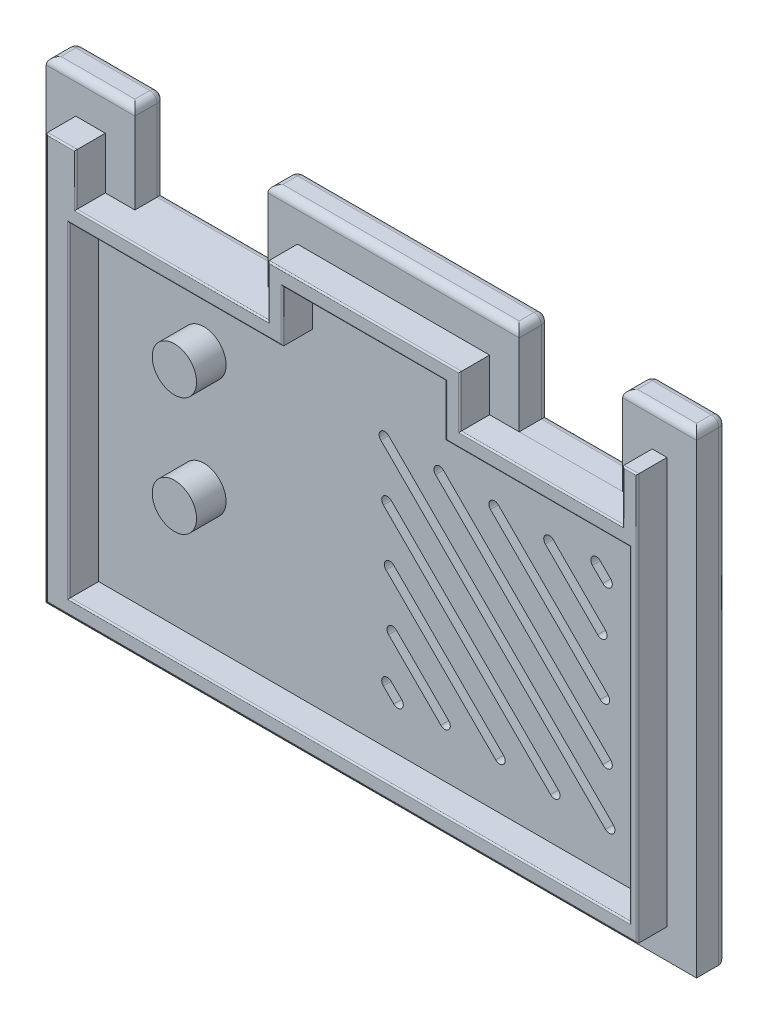
SolidWorks part; units mm, degrees
ref_plane "Front Plane" through (0, 0, 0) normal (0, 0, 1) x (1, 0, 0)
ref_plane "Top Plane" through (0, 0, 0) normal (0, 1, 0) x (1, 0, 0)
ref_plane "Right Plane" through (0, 0, 0) normal (1, 0, 0) x (0, 0, -1)
sketch "Sketch1" plane through (0, 0, 0) normal (0, 0, 1) x (1, 0, 0)
  line L0 (-16, 16) -> (-16, 10)
  line L1 (-22, -16) -> (22, -16)
  line L2 (-22, -16) -> (-22, 16)
  line L3 (-22, 16) -> (-16, 16)
  line L4 (22, -16) -> (22, 16)
  line L5 (-22, -16) -> (22, 16) construction
  line L6 (-22, 16) -> (22, -16) construction
  line L7 (-16, 10) -> (-7, 10)
  line L8 (-7, 10) -> (-7, 16)
  line L9 (10, 16) -> (10, 10)
  line L10 (10, 10) -> (17, 10)
  line L11 (17, 10) -> (17, 16)
  line L12 (-7, 16) -> (10, 16)
  line L13 (17, 16) -> (22, 16)
  point P0 (0, 0)
  dimension "D1" = 44
  dimension "D2" = 32
  dimension "D3" = 6
  dimension "D4" = 15
  dimension "D5" = 5
  dimension "D6" = 12
  dimension "D7" = 6
  dimension "D8" = 6
extrude "Boss-Extrude1" add sketch "Sketch1" along normal blind 2
fillet "Fillet1" radius 0.5 21 edges at (-16, 16, 1) (-16, 13, 0) (17, 16, 1) (17, 13, 0) (-7, 16, 1) (-7, 13, 0) (-11.5, 10, 0) (10, 16, 1) (10, 13, 0) (13.5, 10, 0) (22, 16, 1) (-22, 16, 1) (19.5, 16, 2) (-19, 16, 2) (1.5, 16, 2) (1.5, 16, 0) (-19, 16, 0) (-22, 0, 0) (0, -16, 0) (22, 0, 0) (19.5, 16, 0)
sketch "Sketch2" plane through (0, 0, 2) normal (0, 0, 1) x (1, 0, 0)
  line L24 (20, 13.5) -> (19, 13.5)
  line L25 (20, 13.5) -> (19, 13.5)
  line L26 (-20, 13.5) -> (-20, -14)
  line L27 (-20, -14) -> (20, -14)
  line L28 (20, -14) -> (20, 13.5)
  line L29 (19, 13.5) -> (19, 8)
  line L30 (19, 13.5) -> (19, 10.0029)
  line L31 (19, 8) -> (8, 8)
  line L33 (8, 8) -> (8, 13.5)
  line L34 (8, 10.0029) -> (8, 13.5)
  line L35 (8, 13.5) -> (-5, 13.5)
  line L38 (-20, 13.5) -> (-20, -14)
  line L39 (-20, -14) -> (20, -14)
  line L40 (20, -14) -> (20, 13.5)
  line L48 (-18, 10) -> (-5, 10)
  line L49 (19, 10.0029) -> (8, 10.0029)
  line L50 (7, 9.0029) -> (19.458, 9.0029)
  line L51 (19.458, 9.0029) -> (19.4585, -13)
  line L52 (19.4585, -13) -> (19, -13)
  line L53 (-4, 9.0029) -> (-18.458, 9.0029)
  line L54 (-18.458, 9.0029) -> (-18.458, -13)
  line L55 (-18, 10) -> (-18, 13.5)
  line L60 (-19, 7) -> (-19, -13)
  line L61 (-19, -13) -> (19, -13)
  line L62 (19, -13) -> (19, 7)
  line L63 (19, 7) -> (7, 7)
  line L65 (7, 7) -> (7, 12.5)
  line L66 (7, 9.0029) -> (7, 12.5)
  line L67 (7, 12.5) -> (-4, 12.5)
  line L69 (-18.458, -13) -> (19, -13)
  line L83 (8, 13.5) -> (-5, 13.5)
  line L84 (-5, 13.5) -> (-5, 8)
  line L85 (-5, 13.5) -> (-5, 10)
  line L86 (-5, 8) -> (-18, 8)
  line L88 (-18, 8) -> (-18, 13.5)
  line L90 (-18, 13.5) -> (-20, 13.5)
  line L91 (-18, 13.5) -> (-20, 13.5)
  line L92 (7, 12.5) -> (-4, 12.5)
  line L93 (-4, 12.5) -> (-4, 7)
  line L94 (-4, 12.5) -> (-4, 9.0029)
  line L95 (-4, 7) -> (-19, 7)
  dimension "D3" = 1
  dimension "D1" = 2
  dimension "D2" = 3
extrude "Boss-Extrude2" add sketch "Sketch2" along normal blind 2
fillet "Fillet4" radius 0.1 20 edges at (-11.229, 9.0029, 4) (-18.458, -1.9985, 4) (0.5002, -13, 4) (19.4583, -1.9985, 4) (13.229, 9.0029, 4) (7, 10.7515, 4) (1.5, 12.5, 4) (-4, 10.7515, 4) (19, 11.7515, 4) (19.5, 13.5, 4) (20, -0.25, 4) (0, -14, 4) (-20, -0.25, 4) (-19, 13.5, 4) (-18, 11.75, 4) (-11.5, 10, 4) (-5, 11.75, 4) (1.5, 13.5, 4) (8, 11.7515, 4) (13.5, 10.0029, 4)
sketch "Sketch3" plane through (0, 0, 2) normal (0, 0, 1) x (1, 0, 0)
  line L0 (-11.329, 9.1029) -> (-11.329, -8.234) construction
  line L1 (-18.558, 9.1029) -> (-4.1, 9.1029) construction
  line L2 (-6.5, 16) -> (9.5, 16) construction
  circle A0 centre (-11.329, 4) radius 1.5
  circle A2 centre (-11.329, -4) radius 1.5
  dimension "D1" = 3
  dimension "D2" = 3
  dimension "D3" = 12
  dimension "D4" = 8
extrude "Boss-Extrude3" add sketch "Sketch3" along normal blind 2
sketch "Sketch4" plane through (0, 0, 2) normal (0, 0, 1) x (1, 0, 0)
  line L0 (22, -16) -> (22, 15.5) construction
  line L1 (0, -11) -> (17, -11)
  line L2 (0, -11) -> (0, 6)
  line L4 (17, -11) -> (17, 6)
  line L5 (0, -11) -> (17, 6) construction
  line L6 (0, 6) -> (17, -11) construction
  line L7 (-22, -16) -> (22, -16) construction
  line L8 (0.8986, 5.1014) -> (16.1014, -10.1014) construction
  line L9 (1.1638, 5.3666) -> (16.3666, -9.8362)
  line L10 (0.6334, 4.8362) -> (15.8362, -10.3666)
  line L11 (15.9246, -6.3891) -> (4.6109, 4.9246) construction
  line L12 (15.6595, -6.6543) -> (4.3457, 4.6595)
  line L13 (16.1898, -6.1239) -> (4.8761, 5.1898)
  line L14 (15.7478, -2.6768) -> (8.3232, 4.7478) construction
  line L15 (15.4827, -2.9419) -> (8.0581, 4.4827)
  line L16 (16.013, -2.4116) -> (8.5884, 5.013)
  line L17 (15.5711, 1.0355) -> (12.0355, 4.5711) construction
  line L18 (15.3059, 0.7704) -> (11.7704, 4.3059)
  line L19 (15.8362, 1.3007) -> (12.3007, 4.8362)
  line L20 (15.9246, 4.2175) -> (15.2175, 4.9246) construction
  line L21 (15.6595, 3.9523) -> (14.9523, 4.6595)
  line L22 (16.1898, 4.4827) -> (15.4827, 5.1898)
  line L23 (1.7825, -9.9246) -> (1.0754, -9.2175) construction
  line L24 (2.0477, -9.6595) -> (1.3405, -8.9523)
  line L25 (1.5173, -10.1898) -> (0.8102, -9.4827)
  line L26 (4.9645, -9.5711) -> (1.4289, -6.0355) construction
  line L27 (5.2296, -9.3059) -> (1.6941, -5.7704)
  line L28 (4.6993, -9.8362) -> (1.1638, -6.3007)
  line L29 (8.6768, -9.7478) -> (1.2522, -2.3232) construction
  line L30 (8.9419, -9.4827) -> (1.5173, -2.0581)
  line L31 (8.4116, -10.013) -> (0.987, -2.5884)
  line L32 (12.3891, -9.9246) -> (1.0754, 1.3891) construction
  line L33 (12.6543, -9.6595) -> (1.3405, 1.6543)
  line L34 (12.1239, -10.1898) -> (0.8102, 1.1239)
  arc A0 (1.1638, 5.3666) -> (0.6334, 4.8362) centre (0.8986, 5.1014) ccw
  arc A1 (15.8362, -10.3666) -> (16.3666, -9.8362) centre (16.1014, -10.1014) ccw
  arc A2 (15.6595, -6.6543) -> (16.1898, -6.1239) centre (15.9246, -6.3891) ccw
  arc A3 (4.8761, 5.1898) -> (4.3457, 4.6595) centre (4.6109, 4.9246) ccw
  arc A4 (15.4827, -2.9419) -> (16.013, -2.4116) centre (15.7478, -2.6768) ccw
  arc A5 (8.5884, 5.013) -> (8.0581, 4.4827) centre (8.3232, 4.7478) ccw
  arc A6 (15.3059, 0.7704) -> (15.8362, 1.3007) centre (15.5711, 1.0355) ccw
  arc A7 (12.3007, 4.8362) -> (11.7704, 4.3059) centre (12.0355, 4.5711) ccw
  arc A8 (15.6595, 3.9523) -> (16.1898, 4.4827) centre (15.9246, 4.2175) ccw
  arc A9 (15.4827, 5.1898) -> (14.9523, 4.6595) centre (15.2175, 4.9246) ccw
  arc A10 (2.0477, -9.6595) -> (1.5173, -10.1898) centre (1.7825, -9.9246) cw
  arc A11 (0.8102, -9.4827) -> (1.3405, -8.9523) centre (1.0754, -9.2175) cw
  arc A12 (5.2296, -9.3059) -> (4.6993, -9.8362) centre (4.9645, -9.5711) cw
  arc A13 (1.1638, -6.3007) -> (1.6941, -5.7704) centre (1.4289, -6.0355) cw
  arc A14 (8.9419, -9.4827) -> (8.4116, -10.013) centre (8.6768, -9.7478) cw
  arc A15 (0.987, -2.5884) -> (1.5173, -2.0581) centre (1.2522, -2.3232) cw
  arc A16 (12.6543, -9.6595) -> (12.1239, -10.1898) centre (12.3891, -9.9246) cw
  arc A17 (0.8102, 1.1239) -> (1.3405, 1.6543) centre (1.0754, 1.3891) cw
  point P0 (8.5, -2.5)
  point P11 (8.5, -2.5)
  point P18 (10.2678, -0.7322)
  point P24 (12.0355, 1.0355)
  point P31 (13.8033, 2.8033)
  point P38 (15.5711, 4.5711)
  point P44 (-38.36, 5.2859)
  point P45 (-13.2539, 9.6493)
  point P48 (1.4289, -9.5711)
  point P55 (3.1967, -7.8033)
  point P62 (4.9645, -6.0355)
  point P69 (6.7322, -4.2678)
  dimension "D1" = 5
  dimension "D2" = 5
  dimension "D3" = 0.75
  dimension "D4" = 0.75
  dimension "D5" = 21.5
  dimension "D6" = 16
  dimension "D7" = 2.5
  dimension "D8" = 0.75
  dimension "D9" = 0.75
  dimension "D10" = 0.75
  dimension "D11" = 2.5
  dimension "D12" = 2.5
  dimension "D13" = 2.5
  dimension "D14" = 10.5
  dimension "D15" = 5
  dimension "D16" = 1
extrude "Cut-Extrude4" cut sketch "Sketch4" against normal blind 2 contours L22 A9 L21 A8 | L19 A7 L18 A6 | L16 A5 L15 A4 | L13 A3 L12 A2 | L10 A1 L9 A0 | A17 L34 A16 L33 | A15 L31 A14 L30 | A13 L28 A12 L27 | A11 L25 A10 L24
